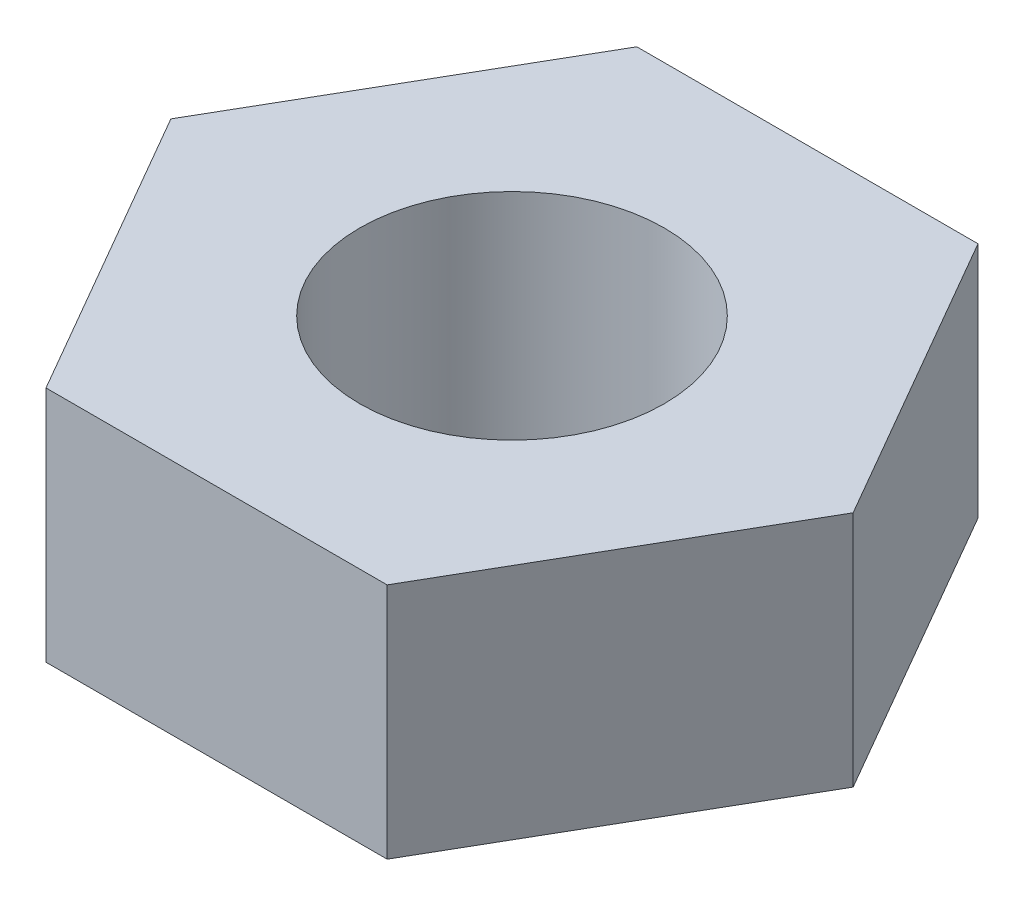
SolidWorks part; units mm, degrees
ref_plane "Front Plane" through (0, 0, 0) normal (0, 0, 1) x (1, 0, 0)
ref_plane "Top Plane" through (0, 0, 0) normal (0, 1, 0) x (1, 0, 0)
ref_plane "Right Plane" through (0, 0, 0) normal (1, 0, 0) x (0, 0, -1)
sketch "Sketch2" plane through (0, 0, 0) normal (0, 1, 0) x (1, 0, 0)
  line L1 (1.4001, -2.425) -> (2.8001, 0)
  line L2 (2.8001, 0) -> (1.4001, 2.425)
  line L3 (1.4001, 2.425) -> (-1.4001, 2.425)
  line L4 (-1.4001, 2.425) -> (-2.8001, 0)
  line L5 (-2.8001, 0) -> (-1.4001, -2.425)
  line L6 (-1.4001, -2.425) -> (1.4001, -2.425)
  circle A0 centre (0, 0) radius 2.425 construction
  circle A1 centre (0, 0) radius 1.25
  dimension "D2" = 2.5
  dimension "D1" = 4.85
extrude "Boss-Extrude1" add sketch "Sketch2" along normal blind 1.95
